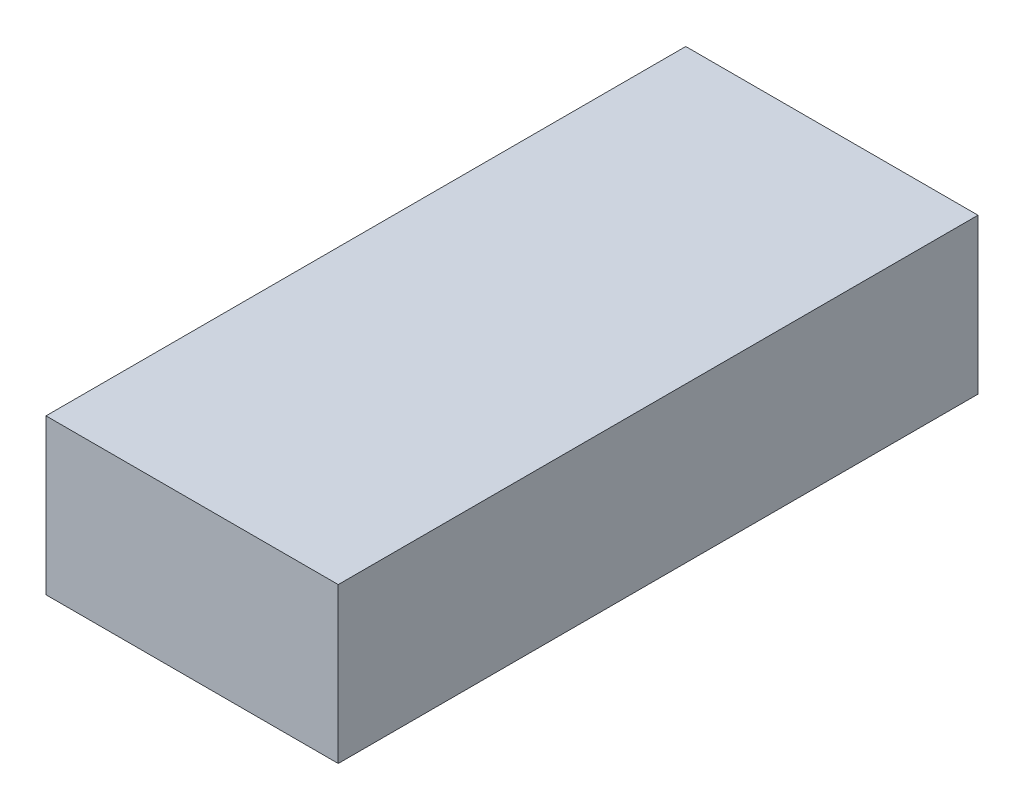
SolidWorks part; units mm, degrees
ref_plane "Front Plane" through (0, 0, 0) normal (0, 0, 1) x (1, 0, 0)
ref_plane "Top Plane" through (0, 0, 0) normal (0, 1, 0) x (1, 0, 0)
ref_plane "Right Plane" through (0, 0, 0) normal (1, 0, 0) x (0, 0, -1)
sketch "Sketch1" plane through (0, 0, 0) normal (0, 1, 0) x (1, 0, 0)
  line L1 (-21.28, 46.585) -> (21.28, 46.585)
  line L2 (-21.28, 46.585) -> (-21.28, -46.585)
  line L3 (-21.28, -46.585) -> (21.28, -46.585)
  line L4 (21.28, 46.585) -> (21.28, -46.585)
  line L5 (-21.28, 46.585) -> (21.28, -46.585) construction
  line L6 (-21.28, -46.585) -> (21.28, 46.585) construction
  point P0 (0, 0)
  dimension "D1" = 93.17
  dimension "D2" = 42.56
extrude "Boss-Extrude1" add sketch "Sketch1" along normal blind 22.57
